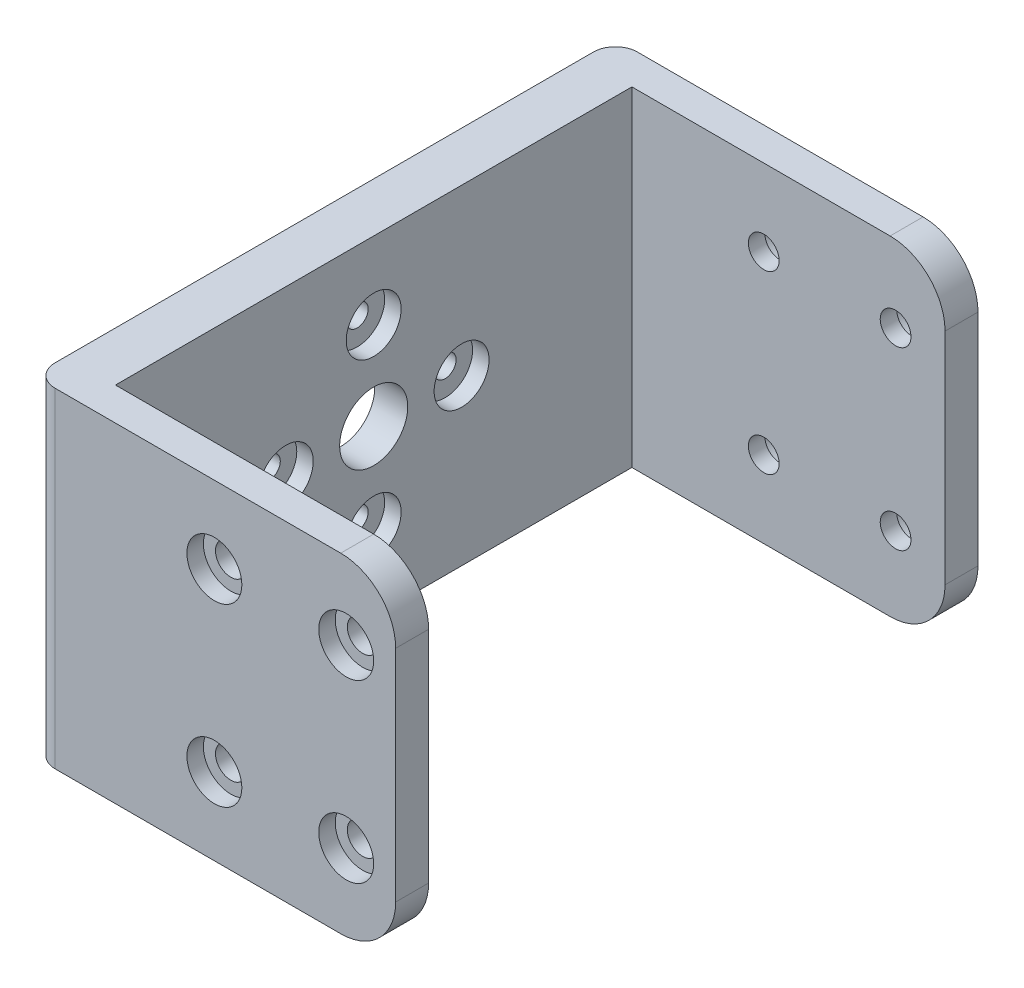
SolidWorks part; units mm, degrees
ref_plane "Front Plane" through (0, 0, 0) normal (0, 0, 1) x (1, 0, 0)
ref_plane "Top Plane" through (0, 0, 0) normal (0, 1, 0) x (1, 0, 0)
ref_plane "Right Plane" through (0, 0, 0) normal (1, 0, 0) x (0, 0, -1)
sketch "Sketch1" plane through (0, 0, 0) normal (0, 1, 0) x (1, 0, 0)
  line L0 (65.8235, -35.5588) -> (65.8235, -32.5588)
  line L1 (65.8235, -32.5588) -> (37.3235, -32.5588)
  line L2 (37.3235, -32.5588) -> (37.3235, 14.4412)
  line L3 (37.3235, 14.4412) -> (65.8235, 14.4412)
  line L4 (65.8235, 14.4412) -> (65.8235, 17.4412)
  line L5 (65.8235, 17.4412) -> (32.8235, 17.4412)
  line L6 (32.8235, 17.4412) -> (32.8235, -35.5588)
  line L7 (32.8235, -35.5588) -> (65.8235, -35.5588)
  dimension "D1" = 3
  dimension "D2" = 4.5
  dimension "D3" = 3
  dimension "D4" = 28.5
  dimension "D5" = 47
extrude "Boss-Extrude1" add sketch "Sketch1" along normal blind 30
sketch "Sketch2" plane through (0, 0, -17.4412) normal (0, 0, -1) x (-1, 0, 0)
  line L0 (-61.3235, 7) -> (-61.3235, 23) construction
  line L1 (-65.8235, 30) -> (-65.8235, 0) construction
  line L2 (-35.8235, 0) -> (-35.8235, 30) construction
  line L3 (-65.8235, 0) -> (-32.8235, 0) construction
  line L4 (-65.8235, 30) -> (-32.8235, 30) construction
  line L5 (-32.8235, 30) -> (-32.8235, 0) construction
  line L6 (-61.3235, 7) -> (-49.3235, 7) construction
  line L7 (-49.3235, 0) -> (-49.3235, 30) construction
  circle A0 centre (-61.3235, 7) radius 1.4
  circle A1 centre (-49.3235, 7) radius 1.4
  circle A2 centre (-49.3235, 23) radius 1.4
  circle A3 centre (-61.3235, 23) radius 1.4
  point P2 (-61.3235, 15)
  point P11 (-65.8235, 15)
  dimension "D1" = 2.8
  dimension "D4" = 3
  dimension "D5" = 12
  dimension "D6" = 16
  dimension "D7" = 12
  dimension "D2" = 2
  dimension "D3" = 2
extrude "Cut-Extrude1" cut sketch "Sketch2" against normal through all
sketch "Sketch3" plane through (0, 0, -17.4412) normal (0, 0, -1) x (-1, 0, 0)
  circle A0 centre (-61.3235, 7) radius 2.5
  circle A1 centre (-49.3235, 7) radius 2.5
  circle A2 centre (-49.3235, 23) radius 2.5
  circle A3 centre (-61.3235, 23) radius 2.5
  point P3 (-58.3235, 23)
  point P4 (0, 0)
  point P5 (-46.3235, 23)
  dimension "D1" = 5
  dimension "D2" = 2
  dimension "D3" = 2
extrude "Cut-Extrude2" cut sketch "Sketch3" against normal blind 1.5
sketch "Sketch5" plane through (32.8235, 0, 0) normal (-1, 0, 0) x (0, 0, 1)
  line L0 (-17.4412, 30) -> (35.5588, 30) construction
  line L1 (-17.4412, 30) -> (-17.4412, 0) construction
  circle A0 centre (9.0588, 15) radius 11.4
  point P5 (9.0588, 30)
  point P9 (-17.4412, 15)
  dimension "D1" = 22.8
extrude "Cut-Extrude4" cut sketch "Sketch5" against normal blind 1.5
sketch "Sketch8" plane through (0, 0, 35.5588) normal (0, 0, 1) x (1, 0, 0)
  circle A0 centre (49.3235, 23) radius 2.5
  circle A1 centre (61.3235, 23) radius 2.5
  circle A2 centre (49.3235, 7) radius 2.5
  circle A3 centre (61.3235, 7) radius 2.5
  point P5 (58.3235, 23)
  point P9 (46.3235, 7)
  point P13 (58.3235, 7)
  dimension "D1" = 5
extrude "Cut-Extrude7" cut sketch "Sketch8" against normal blind 1.5
sketch "Sketch6" plane through (34.3235, 0, 0) normal (-1, 0, 0) x (0, 0, 1)
  circle A0 centre (9.0588, 15) radius 3.1
  circle A1 centre (9.0588, 15) radius 8 construction
  circle A2 centre (1.0588, 15) radius 1
  circle A3 centre (9.0588, 23) radius 1
  circle A4 centre (17.0588, 15) radius 1
  circle A5 centre (9.0588, 7) radius 1
  point P15 (9.0588, 15)
  dimension "D1" = 6.2
  dimension "D2" = 16
  dimension "D3" = 2
  dimension "D4" = 4
extrude "Cut-Extrude5" cut sketch "Sketch6" against normal through all
fillet "Fillet1" radius 5 4 edges at (65.8235, 0, 34.0588) (65.8235, 30, 34.0588) (65.8235, 0, -15.9412) (65.8235, 30, -15.9412)
fillet "Fillet2" radius 2 2 edges at (32.8235, 15, 35.5588) (32.8235, 15, -17.4412)
sketch "Sketch7" plane through (37.3235, 0, 0) normal (1, 0, 0) x (0, 0, -1)
  circle A0 centre (-17.0588, 15) radius 2.5
  circle A1 centre (-9.0588, 23) radius 2.5
  circle A2 centre (-1.0588, 15) radius 2.5
  circle A3 centre (-9.0588, 7) radius 2.5
  point P12 (-9.0588, 15)
  dimension "D1" = 5
  dimension "D2" = 4
extrude "Cut-Extrude6" cut sketch "Sketch7" against normal blind 1.5
